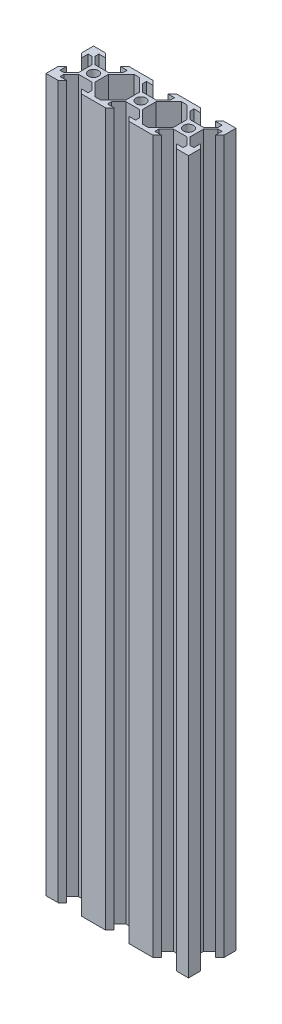
SolidWorks part; units mm, degrees
ref_plane "前视基准面" through (0, 0, 0) normal (0, 0, 1) x (1, 0, 0)
ref_plane "上视基准面" through (0, 0, 0) normal (0, 1, 0) x (1, 0, 0)
ref_plane "右视基准面" through (0, 0, 0) normal (1, 0, 0) x (0, 0, -1)
sketch "草图1" plane through (0, 0, 0) normal (0, 1, 0) x (1, 0, 0)
  line L0 (-25.721, 0) -> (73.7722, 0)
  line L1 (0, 21.255) -> (0, -16.6235)
  line L2 (-10, 21.255) -> (-10, -16.6235)
  line L3 (-25.721, 10) -> (73.7722, 10)
  line L4 (-4.9, 10) -> (-3.1, 8.2)
  line L5 (-3.1, 8.2) -> (-5.9236, 8.2)
  line L6 (-5.9236, 8.2) -> (-5.9236, 6.56)
  line L7 (-5.9236, 6.56) -> (-2.84, 3.4764)
  line L8 (-2.84, 3.4764) -> (2.84, 3.4764)
  line L9 (-10, 10) -> (0, 0) construction
  line L10 (5.9236, 6.56) -> (2.84, 3.4764)
  line L11 (5.9236, 8.2) -> (5.9236, 6.56)
  line L12 (3.1, 8.2) -> (5.9236, 8.2)
  line L13 (4.9, 10) -> (3.1, 8.2)
  line L14 (-10, -4.9) -> (-8.2, -3.1)
  line L15 (-8.2, -3.1) -> (-8.2, -5.9236)
  line L16 (-8.2, -5.9236) -> (-6.56, -5.9236)
  line L17 (-6.56, -5.9236) -> (-3.4764, -2.84)
  line L18 (-3.4764, 2.84) -> (-3.4764, -2.84)
  line L19 (-6.56, 5.9236) -> (-3.4764, 2.84)
  line L20 (-8.2, 5.9236) -> (-6.56, 5.9236)
  line L21 (-8.2, 3.1) -> (-8.2, 5.9236)
  line L22 (-10, 4.9) -> (-8.2, 3.1)
  line L23 (-25.721, -10) -> (73.7722, -10)
  line L24 (4.9, -10) -> (3.1, -8.2)
  line L25 (3.1, -8.2) -> (5.9236, -8.2)
  line L26 (5.9236, -8.2) -> (5.9236, -6.56)
  line L27 (5.9236, -6.56) -> (2.84, -3.4764)
  line L28 (-2.84, -3.4764) -> (2.84, -3.4764)
  line L29 (-5.9236, -6.56) -> (-2.84, -3.4764)
  line L30 (-5.9236, -8.2) -> (-5.9236, -6.56)
  line L31 (-3.1, -8.2) -> (-5.9236, -8.2)
  line L32 (-4.9, -10) -> (-3.1, -8.2)
  line L33 (50, 21.255) -> (50, -16.6235)
  line L34 (20, 21.255) -> (20, -16.6235)
  line L35 (10, 4.9) -> (8.2, 3.1)
  line L36 (8.2, 3.1) -> (8.2, 5.9236)
  line L37 (8.2, 5.9236) -> (6.56, 5.9236)
  line L38 (6.56, 5.9236) -> (3.4764, 2.84)
  line L39 (3.4764, 2.84) -> (3.4764, -2.84)
  line L40 (6.56, -5.9236) -> (3.4764, -2.84)
  line L41 (8.2, -5.9236) -> (6.56, -5.9236)
  line L42 (8.2, -3.1) -> (8.2, -5.9236)
  line L43 (10, -4.9) -> (8.2, -3.1)
  line L44 (15.1, 10) -> (16.9, 8.2)
  line L45 (16.9, 8.2) -> (14.0764, 8.2)
  line L46 (14.0764, 8.2) -> (14.0764, 6.56)
  line L47 (14.0764, 6.56) -> (17.16, 3.4764)
  line L48 (17.16, 3.4764) -> (22.84, 3.4764)
  line L49 (25.9236, 6.56) -> (22.84, 3.4764)
  line L50 (25.9236, 8.2) -> (25.9236, 6.56)
  line L51 (23.1, 8.2) -> (25.9236, 8.2)
  line L52 (24.9, 10) -> (23.1, 8.2)
  line L53 (10, -4.9) -> (11.8, -3.1)
  line L54 (11.8, -3.1) -> (11.8, -5.9236)
  line L55 (11.8, -5.9236) -> (13.44, -5.9236)
  line L56 (13.44, -5.9236) -> (16.5236, -2.84)
  line L57 (16.5236, 2.84) -> (16.5236, -2.84)
  line L58 (13.44, 5.9236) -> (16.5236, 2.84)
  line L59 (11.8, 5.9236) -> (13.44, 5.9236)
  line L60 (11.8, 3.1) -> (11.8, 5.9236)
  line L61 (10, 4.9) -> (11.8, 3.1)
  line L62 (24.9, -10) -> (23.1, -8.2)
  line L63 (23.1, -8.2) -> (25.9236, -8.2)
  line L64 (25.9236, -8.2) -> (25.9236, -6.56)
  line L65 (25.9236, -6.56) -> (22.84, -3.4764)
  line L66 (17.16, -3.4764) -> (22.84, -3.4764)
  line L67 (14.0764, -6.56) -> (17.16, -3.4764)
  line L68 (14.0764, -8.2) -> (14.0764, -6.56)
  line L69 (16.9, -8.2) -> (14.0764, -8.2)
  line L70 (15.1, -10) -> (16.9, -8.2)
  line L71 (30, 4.9) -> (28.2, 3.1)
  line L72 (28.2, 3.1) -> (28.2, 5.9236)
  line L73 (28.2, 5.9236) -> (26.56, 5.9236)
  line L74 (26.56, 5.9236) -> (23.4764, 2.84)
  line L75 (23.4764, 2.84) -> (23.4764, -2.84)
  line L76 (26.56, -5.9236) -> (23.4764, -2.84)
  line L77 (28.2, -5.9236) -> (26.56, -5.9236)
  line L78 (28.2, -3.1) -> (28.2, -5.9236)
  line L79 (30, -4.9) -> (28.2, -3.1)
  line L80 (6.56, 5.9236) -> (8.8364, 8.2)
  line L81 (35.1, 10) -> (36.9, 8.2)
  line L82 (36.9, 8.2) -> (34.0764, 8.2)
  line L83 (34.0764, 8.2) -> (34.0764, 6.56)
  line L84 (34.0764, 6.56) -> (37.16, 3.4764)
  line L85 (37.16, 3.4764) -> (42.84, 3.4764)
  line L86 (45.9236, 6.56) -> (42.84, 3.4764)
  line L87 (45.9236, 8.2) -> (45.9236, 6.56)
  line L88 (43.1, 8.2) -> (45.9236, 8.2)
  line L89 (44.9, 10) -> (43.1, 8.2)
  line L90 (30, -4.9) -> (31.8, -3.1)
  line L91 (31.8, -3.1) -> (31.8, -5.9236)
  line L92 (31.8, -5.9236) -> (33.44, -5.9236)
  line L93 (33.44, -5.9236) -> (36.5236, -2.84)
  line L94 (36.5236, 2.84) -> (36.5236, -2.84)
  line L95 (33.44, 5.9236) -> (36.5236, 2.84)
  line L96 (31.8, 5.9236) -> (33.44, 5.9236)
  line L97 (31.8, 3.1) -> (31.8, 5.9236)
  line L98 (30, 4.9) -> (31.8, 3.1)
  line L99 (44.9, -10) -> (43.1, -8.2)
  line L100 (43.1, -8.2) -> (45.9236, -8.2)
  line L101 (45.9236, -8.2) -> (45.9236, -6.56)
  line L102 (45.9236, -6.56) -> (42.84, -3.4764)
  line L103 (37.16, -3.4764) -> (42.84, -3.4764)
  line L104 (34.0764, -6.56) -> (37.16, -3.4764)
  line L105 (34.0764, -8.2) -> (34.0764, -6.56)
  line L106 (36.9, -8.2) -> (34.0764, -8.2)
  line L107 (35.1, -10) -> (36.9, -8.2)
  line L108 (50, 4.9) -> (48.2, 3.1)
  line L109 (48.2, 3.1) -> (48.2, 5.9236)
  line L110 (48.2, 5.9236) -> (46.56, 5.9236)
  line L111 (46.56, 5.9236) -> (43.4764, 2.84)
  line L112 (43.4764, 2.84) -> (43.4764, -2.84)
  line L113 (46.56, -5.9236) -> (43.4764, -2.84)
  line L114 (48.2, -5.9236) -> (46.56, -5.9236)
  line L115 (48.2, -3.1) -> (48.2, -5.9236)
  line L116 (50, -4.9) -> (48.2, -3.1)
  line L117 (13.44, 5.9236) -> (11.1636, 8.2)
  line L118 (30, 10) -> (40, 0) construction
  line L119 (10, 10) -> (20, 0) construction
  line L120 (8.8364, 8.2) -> (11.1636, 8.2)
  line L121 (8.8364, -8.2) -> (11.1636, -8.2)
  line L122 (6.56, -5.9236) -> (8.8364, -8.2)
  line L123 (13.44, -5.9236) -> (11.1636, -8.2)
  line L124 (26.56, 5.9236) -> (28.8364, 8.2)
  line L125 (28.8364, 8.2) -> (31.1636, 8.2)
  line L126 (33.44, 5.9236) -> (31.1636, 8.2)
  line L127 (26.56, -5.9236) -> (28.8364, -8.2)
  line L128 (28.8364, -8.2) -> (31.1636, -8.2)
  line L129 (33.44, -5.9236) -> (31.1636, -8.2)
  circle A0 centre (0, 0) radius 2.1
  circle A1 centre (20, 0) radius 2.1
  circle A2 centre (40, 0) radius 2.1
  circle A3 centre (20, 0) radius 2.1
  circle A4 centre (40, 0) radius 2.1
  point P22 (0, 3.4764)
  point P37 (-3.4764, 0)
  point P50 (0, -3.4764)
  point P65 (3.4764, 0)
  point P77 (20, 3.4764)
  point P92 (16.5236, 0)
  point P103 (20, -3.4764)
  point P114 (23.4764, 0)
  point P124 (40, 3.4764)
  point P139 (36.5236, 0)
  point P150 (40, -3.4764)
  point P161 (43.4764, 0)
  dimension "D1" = 3
  dimension "D2" = 4.2
  dimension "D3" = 20
  dimension "D6" = 1.8
  dimension "D7" = 1.64
  dimension "D8" = 2.84
  dimension "D9" = 3.1
  dimension "D10" = 45
  dimension "D11" = 0.9
  dimension "D16" = 2
  dimension "D4" = 10
  dimension "D5" = 10
  dimension "D12" = 10
  dimension "D13" = 60
  dimension "D14" = 30
  dimension "D15" = 3
extrude "凸台-拉伸1" add sketch "草图1" along normal blind 300 contours A0 L1 L8 L7 L6 L5 L4 L3 L2 L22 L21 L20 L19 L18 L0 | A0 L0 L18 L17 L16 L15 L14 L2 L23 L32 L31 L30 L29 L28 L1 | A1 L0 L57 L56 L123 L121 L122 L40 L39 A0 L1 L28 L27 L26 L25 L24 L23 L70 L69 L68 L67 L66 L34 | A1 L34 L48 L47 L46 L45 L44 L3 L13 L12 L11 L10 L8 L1 A0 L0 L39 L38 L80 L120 L117 L58 L57 | A2 L0 L112 L111 L110 L109 L108 L33 L3 L89 L88 L87 L86 L85 L84 L83 L82 L81 L52 L51 L50 L49 L48 L34 A1 L75 L74 L124 L125 L126 L95 L94 | A2 L0 L94 L93 L129 L128 L127 L76 L75 A1 L34 L66 L65 L64 L63 L62 L23 L107 L106 L105 L104 L103 L102 L101 L100 L99 L33 L116 L115 L114 L113 L112
